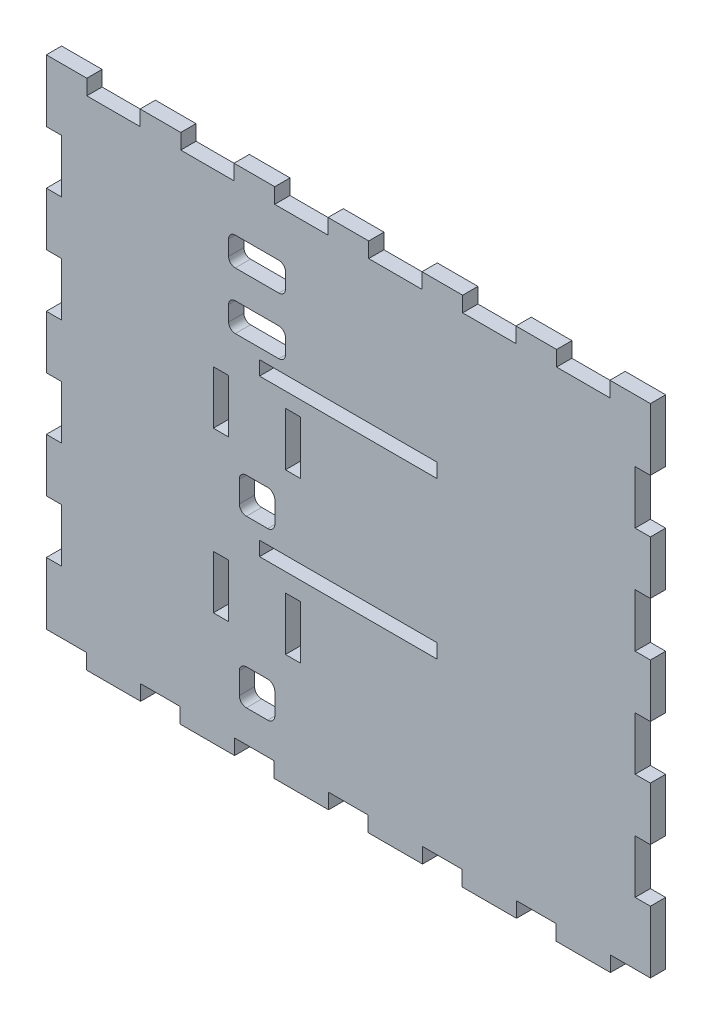
SolidWorks part; units mm, degrees
ref_plane "Front Plane" through (0, 0, 0) normal (0, 0, 1) x (1, 0, 0)
ref_plane "Top Plane" through (0, 0, 0) normal (0, 1, 0) x (1, 0, 0)
ref_plane "Right Plane" through (0, 0, 0) normal (1, 0, 0) x (0, 0, -1)
sketch "Sketch1" plane through (0, 0, 0) normal (0, 0, 1) x (1, 0, 0)
  line L31 (0, 140) -> (11.393, 140)
  line L61 (85, 140) -> (85, 0) construction
  line L92 (26.393, 140) -> (37.836, 140)
  line L93 (11.393, 135.7) -> (26.393, 135.7)
  line L94 (11.393, 135.7) -> (11.393, 140)
  line L96 (26.393, 135.7) -> (26.393, 140)
  line L97 (52.836, 135.7) -> (52.836, 140)
  line L98 (37.836, 135.7) -> (52.836, 135.7)
  line L99 (37.836, 135.7) -> (37.836, 140)
  line L100 (79.279, 135.7) -> (79.279, 140)
  line L101 (64.279, 135.7) -> (79.279, 135.7)
  line L102 (64.279, 135.7) -> (64.279, 140)
  line L103 (105.722, 135.7) -> (105.722, 140)
  line L104 (90.722, 135.7) -> (105.722, 135.7)
  line L105 (90.722, 135.7) -> (90.722, 140)
  line L106 (132.165, 135.7) -> (132.165, 140)
  line L107 (117.165, 135.7) -> (132.165, 135.7)
  line L108 (117.165, 135.7) -> (117.165, 140)
  line L109 (158.608, 135.7) -> (158.608, 140)
  line L110 (143.608, 135.7) -> (158.608, 135.7)
  line L111 (143.608, 135.7) -> (143.608, 140)
  line L112 (52.836, 140) -> (64.279, 140)
  line L113 (79.279, 140) -> (90.722, 140)
  line L114 (105.722, 140) -> (117.165, 140)
  line L115 (132.165, 140) -> (143.608, 140)
  line L116 (158.608, 140) -> (170, 140)
  line L141 (0, 0) -> (11.243, 0)
  line L142 (26.543, 0) -> (37.686, 0)
  line L143 (11.243, -4.3) -> (26.543, -4.3)
  line L144 (11.243, -4.3) -> (11.243, 0)
  line L146 (26.543, -4.3) -> (26.543, 0)
  line L147 (52.986, -4.3) -> (52.986, 0)
  line L148 (37.686, -4.3) -> (52.986, -4.3)
  line L149 (37.686, -4.3) -> (37.686, 0)
  line L150 (79.429, -4.3) -> (79.429, 0)
  line L151 (64.129, -4.3) -> (79.429, -4.3)
  line L152 (64.129, -4.3) -> (64.129, 0)
  line L153 (105.872, -4.3) -> (105.872, 0)
  line L154 (90.572, -4.3) -> (105.872, -4.3)
  line L155 (90.572, -4.3) -> (90.572, 0)
  line L156 (132.315, -4.3) -> (132.315, 0)
  line L157 (117.015, -4.3) -> (132.315, -4.3)
  line L158 (117.015, -4.3) -> (117.015, 0)
  line L159 (158.758, -4.3) -> (158.758, 0)
  line L160 (143.458, -4.3) -> (158.758, -4.3)
  line L161 (143.458, -4.3) -> (143.458, 0)
  line L162 (52.986, 0) -> (64.129, 0)
  line L163 (79.429, 0) -> (90.572, 0)
  line L164 (105.872, 0) -> (117.015, 0)
  line L165 (132.315, 0) -> (143.458, 0)
  line L166 (158.758, 0) -> (170, 0)
  line L179 (170, 122.5) -> (170, 140)
  line L180 (165.7, 107.5) -> (170, 107.5)
  line L181 (170, 0) -> (170, 17.5)
  line L182 (165.7, 107.5) -> (165.7, 122.5)
  line L183 (165.7, 122.5) -> (170, 122.5)
  line L184 (165.7, 77.5) -> (170, 77.5)
  line L185 (165.7, 92.5) -> (170, 92.5)
  line L186 (165.7, 77.5) -> (165.7, 92.5)
  line L187 (165.7, 47.5) -> (170, 47.5)
  line L188 (165.7, 62.5) -> (170, 62.5)
  line L189 (165.7, 47.5) -> (165.7, 62.5)
  line L190 (165.7, 17.5) -> (170, 17.5)
  line L191 (165.7, 32.5) -> (170, 32.5)
  line L192 (165.7, 17.5) -> (165.7, 32.5)
  line L193 (71.6, 27.5) -> (67.3, 27.5)
  line L194 (71.6, 72.5) -> (67.3, 72.5)
  line L195 (51.3, 72.5) -> (47, 72.5)
  line L196 (51.3, 72.5) -> (51.3, 87.5)
  line L197 (170, 32.5) -> (170, 47.5)
  line L198 (170, 62.5) -> (170, 77.5)
  line L199 (170, 92.5) -> (170, 107.5)
  line L200 (0, 92.5) -> (0, 107.5)
  line L201 (0, 62.5) -> (0, 77.5)
  line L202 (0, 32.5) -> (0, 47.5)
  line L203 (51.3, 87.5) -> (47, 87.5)
  line L204 (47, 72.5) -> (47, 87.5)
  line L205 (51.3, 72.5) -> (47, 87.5) construction
  line L206 (51.3, 87.5) -> (47, 72.5) construction
  line L207 (4.3, 17.5) -> (4.3, 32.5)
  line L208 (4.3, 32.5) -> (0, 32.5)
  line L209 (4.3, 17.5) -> (0, 17.5)
  line L210 (4.3, 47.5) -> (4.3, 62.5)
  line L211 (4.3, 62.5) -> (0, 62.5)
  line L212 (4.3, 47.5) -> (0, 47.5)
  line L213 (4.3, 77.5) -> (4.3, 92.5)
  line L214 (4.3, 92.5) -> (0, 92.5)
  line L215 (4.3, 77.5) -> (0, 77.5)
  line L216 (4.3, 122.5) -> (0, 122.5)
  line L217 (4.3, 107.5) -> (4.3, 122.5)
  line L218 (0, 0) -> (0, 17.5)
  line L219 (4.3, 107.5) -> (0, 107.5)
  line L220 (0, 122.5) -> (0, 140)
  line L221 (60, 51.7) -> (110, 51.7)
  line L222 (60, 47.7) -> (60, 51.7)
  line L223 (110, 47.7) -> (60, 47.7)
  line L224 (60, 95.7) -> (110, 95.7)
  line L225 (110, 95.7) -> (110, 91.7)
  line L226 (110, 91.7) -> (60, 91.7)
  line L227 (53.1737, 114.65) -> (65.4263, 114.65)
  line L228 (51.3, 116.5237) -> (51.3, 120.7763)
  line L229 (53.1737, 122.65) -> (65.4263, 122.65)
  line L230 (67.3, 116.5237) -> (67.3, 120.7763)
  line L231 (51.3, 114.65) -> (67.3, 122.65) construction
  line L232 (51.3, 122.65) -> (67.3, 114.65) construction
  line L233 (53.1737, 98.65) -> (65.4263, 98.65)
  line L234 (51.3, 100.5237) -> (51.3, 104.7763)
  line L235 (53.1737, 106.65) -> (65.4263, 106.65)
  line L236 (67.3, 100.5237) -> (67.3, 104.7763)
  line L237 (51.3, 98.65) -> (67.3, 106.65) construction
  line L238 (51.3, 106.65) -> (67.3, 98.65) construction
  line L239 (71.6, 72.5) -> (71.6, 87.5)
  line L244 (51.3, 27.5) -> (47, 27.5)
  line L245 (51.3, 27.5) -> (51.3, 42.5)
  line L250 (51.3, 42.5) -> (47, 42.5)
  line L251 (47, 27.5) -> (47, 42.5)
  line L260 (110, 47.7) -> (110, 51.7)
  line L261 (60, 91.7) -> (60, 95.7)
  line L262 (71.6, 87.5) -> (67.3, 87.5)
  line L263 (67.3, 72.5) -> (67.3, 87.5)
  line L268 (71.6, 72.5) -> (67.3, 87.5) construction
  line L269 (71.6, 87.5) -> (67.3, 72.5) construction
  line L270 (51.3, 27.5) -> (47, 42.5) construction
  line L271 (51.3, 42.5) -> (47, 27.5) construction
  line L272 (71.6, 27.5) -> (71.6, 42.5)
  line L273 (71.6, 42.5) -> (67.3, 42.5)
  line L274 (67.3, 27.5) -> (67.3, 42.5)
  line L275 (71.6, 27.5) -> (67.3, 42.5) construction
  line L276 (71.6, 42.5) -> (67.3, 27.5) construction
  line L278 (56.3, 9) -> (62.3, 9)
  line L279 (54.3, 11) -> (54.3, 17)
  line L280 (56.3, 19) -> (62.3, 19)
  line L281 (64.3, 11) -> (64.3, 17)
  line L282 (54.3, 9) -> (64.3, 19) construction
  line L283 (54.3, 19) -> (64.3, 9) construction
  line L284 (56.3, 65.7) -> (62.3, 65.7)
  line L285 (54.3, 63.7) -> (54.3, 57.7)
  line L286 (56.3, 55.7) -> (62.3, 55.7)
  line L287 (64.3, 63.7) -> (64.3, 57.7)
  line L288 (54.3, 65.7) -> (64.3, 55.7) construction
  line L289 (54.3, 55.7) -> (64.3, 65.7) construction
  circle A0 centre (59.3, 110.65) radius 15 construction
  arc A9 (53.1737, 106.65) -> (51.3, 104.7763) centre (53.1737, 104.7763) ccw
  arc A10 (51.3, 100.5237) -> (53.1737, 98.65) centre (53.1737, 100.5237) ccw
  arc A11 (65.4263, 98.65) -> (67.3, 100.5237) centre (65.4263, 100.5237) ccw
  arc A12 (67.3, 104.7763) -> (65.4263, 106.65) centre (65.4263, 104.7763) ccw
  arc A13 (67.3, 120.7763) -> (65.4263, 122.65) centre (65.4263, 120.7763) ccw
  arc A14 (67.3, 116.5237) -> (65.4263, 114.65) centre (65.4263, 116.5237) cw
  arc A15 (51.3, 116.5237) -> (53.1737, 114.65) centre (53.1737, 116.5237) ccw
  arc A16 (51.3, 120.7763) -> (53.1737, 122.65) centre (53.1737, 120.7763) cw
  arc A17 (62.3, 19) -> (64.3, 17) centre (62.3, 17) cw
  arc A18 (64.3, 11) -> (62.3, 9) centre (62.3, 11) cw
  arc A19 (56.3, 9) -> (54.3, 11) centre (56.3, 11) cw
  arc A20 (54.3, 17) -> (56.3, 19) centre (56.3, 17) cw
  arc A21 (54.3, 57.7) -> (56.3, 55.7) centre (56.3, 57.7) ccw
  arc A22 (62.3, 55.7) -> (64.3, 57.7) centre (62.3, 57.7) ccw
  arc A23 (64.3, 63.7) -> (62.3, 65.7) centre (62.3, 63.7) ccw
  arc A24 (56.3, 65.7) -> (54.3, 63.7) centre (56.3, 63.7) ccw
  point P4 (59.3, 118.65)
  point P23 (165.7, 115)
  point P24 (69.45, 80)
  point P25 (165.7, 85)
  point P32 (49.15, 80)
  point P63 (85, 51.7)
  point P122 (69.45, 35)
  point P123 (59.3, 60.7)
  point P125 (18.893, -4.3)
  point P127 (49.15, 35)
  point P136 (59.3, 14)
  point P137 (60, 49.7)
  point P138 (59.3, 102.65)
  point P139 (45.336, -4.3)
  dimension "D27" = 30
  dimension "D40" = 35
  dimension "D41" = 1.8737
  dimension "D51" = 2
  dimension "D1" = 140
  dimension "D2" = 170
  dimension "D3" = 4.3
  dimension "D4" = 11.393
  dimension "D5" = 4.3
  dimension "D7" = 30
  dimension "D8" = 15
  dimension "D9" = 4
  dimension "D10" = 25
  dimension "D12" = 11.443
  dimension "D13" = 15.3
  dimension "D14" = 4.3
  dimension "D15" = 18.893
  dimension "D17" = 26.443
  dimension "D18" = 4
  dimension "D19" = 4
  dimension "D20" = 47.7
  dimension "D21" = 40
  dimension "D22" = 85
  dimension "D23" = 16
  dimension "D24" = 8
  dimension "D6" = 15
  dimension "D25" = 16
  dimension "D26" = 8
  dimension "D28" = 16
  dimension "D29" = 4.3
  dimension "D30" = 4.3
  dimension "D31" = 16
  dimension "D32" = 4.3
  dimension "D33" = 8
  dimension "D34" = 8
  dimension "D35" = 4.3
  dimension "D36" = 8
  dimension "D37" = 55
  dimension "D38" = 14.95
  dimension "D39" = 50
  dimension "D42" = 15
  dimension "D43" = 15
  dimension "D44" = 80
  dimension "D45" = 8
  dimension "D46" = 10
  dimension "D47" = 10
  dimension "D48" = 10
  dimension "D49" = 14
  dimension "D50" = 9
  dimension "D11" = 6
  dimension "D16" = 6
extrude "Boss-Extrude1" add sketch "Sketch1" along normal blind 4.3
